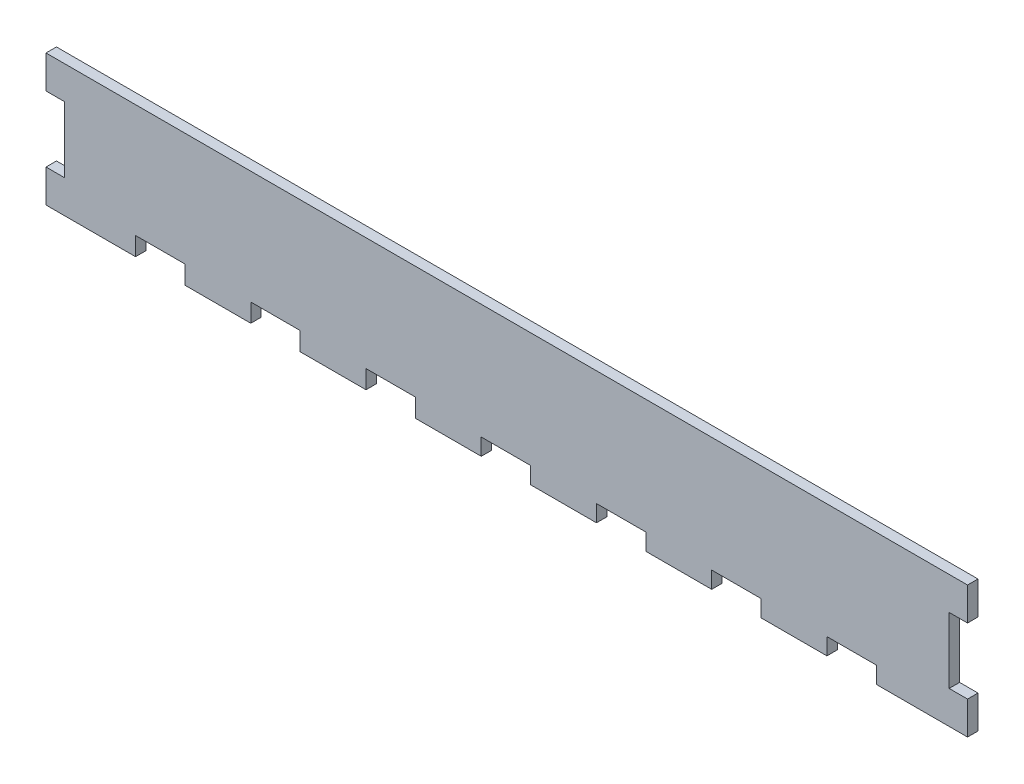
SolidWorks part; units mm, degrees
ref_plane "Front Plane" through (0, 0, 0) normal (0, 0, 1) x (1, 0, 0)
ref_plane "Top Plane" through (0, 0, 0) normal (0, 1, 0) x (1, 0, 0)
ref_plane "Right Plane" through (0, 0, 0) normal (1, 0, 0) x (0, 0, -1)
sketch "Sketch27" plane through (0, 0, 0) normal (0, 0, 1) x (1, 0, 0)
  line L1 (-5.3307, -226.482) -> (274.5773, -226.482)
  line L2 (-5.3307, -266.482) -> (-5.3307, -256.482)
  line L3 (-5.3307, -266.482) -> (21.8693, -266.482)
  line L4 (274.5773, -226.482) -> (274.5773, -236.482)
  line L5 (268.9893, -236.482) -> (274.5773, -236.482)
  line L6 (268.9893, -236.482) -> (268.9893, -256.482)
  line L7 (268.9893, -256.482) -> (274.5773, -256.482)
  line L8 (246.8652, -266.482) -> (274.5773, -266.482)
  line L9 (-5.3307, -236.482) -> (0.2573, -236.482)
  line L10 (274.5773, -256.482) -> (274.5773, -266.482)
  line L12 (0.2573, -236.482) -> (0.2573, -256.482)
  line L14 (-5.3307, -226.482) -> (-5.3307, -236.482)
  line L16 (211.8693, -266.482) -> (231.8653, -266.482)
  line L17 (-5.3307, -256.482) -> (0.2573, -256.482)
  line L20 (176.8653, -266.482) -> (196.8693, -266.482)
  line L21 (21.8693, -260.894) -> (36.8693, -260.894)
  line L22 (21.8693, -260.894) -> (21.8693, -266.482)
  line L24 (36.8693, -260.894) -> (36.8693, -266.482)
  line L25 (56.8734, -260.894) -> (71.8693, -260.894)
  line L26 (56.8734, -260.894) -> (56.8734, -266.482)
  line L27 (36.8693, -266.482) -> (56.8734, -266.482)
  line L28 (71.8693, -260.894) -> (71.8693, -266.482)
  line L30 (91.8693, -260.894) -> (106.8733, -260.894)
  line L31 (91.8693, -260.894) -> (91.8693, -266.482)
  line L32 (71.8693, -266.482) -> (91.8693, -266.482)
  line L33 (106.8733, -260.894) -> (106.8733, -266.482)
  line L34 (126.8693, -261.402) -> (141.8653, -261.402)
  line L35 (126.8693, -261.402) -> (126.8693, -266.482)
  line L36 (106.8733, -266.482) -> (126.8693, -266.482)
  line L38 (141.8653, -261.402) -> (141.8653, -266.482)
  line L39 (161.8653, -261.402) -> (176.8653, -261.402)
  line L40 (161.8653, -261.402) -> (161.8653, -266.482)
  line L42 (141.8653, -266.482) -> (161.8653, -266.482)
  line L43 (176.8653, -261.402) -> (176.8653, -266.482)
  line L44 (196.8693, -261.402) -> (211.8693, -261.402)
  line L45 (196.8693, -261.402) -> (196.8693, -266.482)
  line L52 (211.8693, -261.402) -> (211.8693, -266.482)
  line L53 (231.8653, -261.402) -> (246.8652, -261.402)
  line L54 (231.8653, -261.402) -> (231.8653, -266.482)
  line L56 (246.8652, -261.402) -> (246.8652, -266.482)
  dimension "D1" = 5.588
  dimension "D2" = 5.588
  dimension "D3" = 5.588
  dimension "D4" = 5.588
  dimension "D5" = 5.588
extrude "Boss-Extrude1" add sketch "Sketch27" along normal blind 3.175
